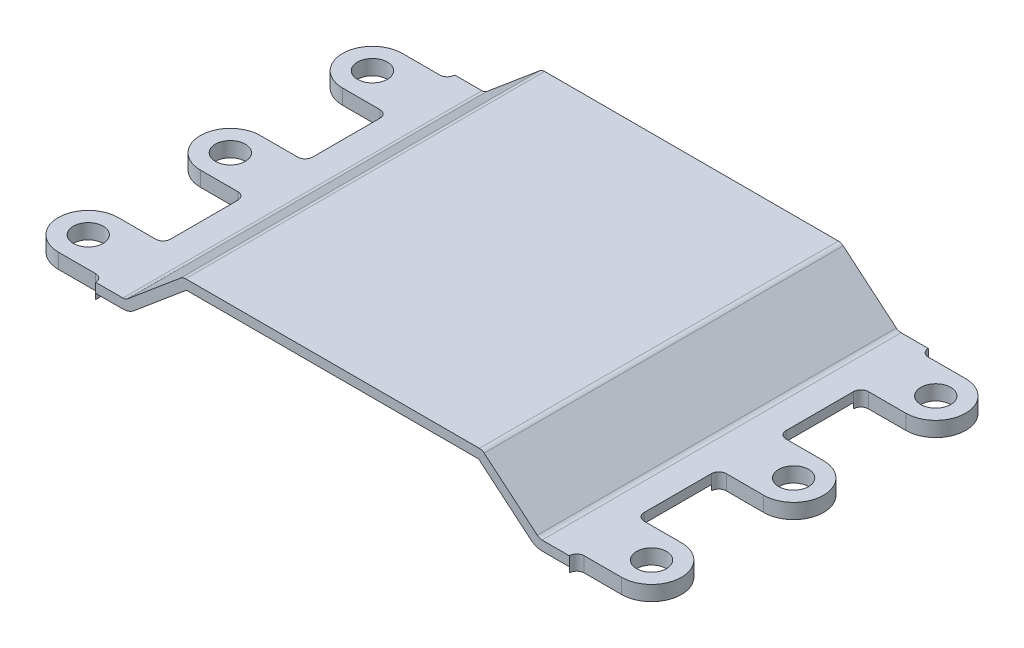
SolidWorks part; units mm, degrees
ref_plane "Front Plane" through (0, 0, 0) normal (0, 0, 1) x (1, 0, 0)
ref_plane "Top Plane" through (0, 0, 0) normal (0, 1, 0) x (1, 0, 0)
ref_plane "Right Plane" through (0, 0, 0) normal (1, 0, 0) x (0, 0, -1)
sketch "Sketch1" plane through (0, 0, 0) normal (0, 0, 1) x (1, 0, 0)
  line L0 (92.7015, 0) -> (86.9293, 0)
  line L1 (85.9089, 0.3714) -> (74.6414, 9.826)
  line L2 (73.621, 10.1974) -> (11.2766, 10.1974)
  line L3 (42.4488, 10.1974) -> (42.4488, 47.8596) construction
  line L4 (-7.804, 0) -> (-2.0318, 0)
  line L5 (-1.0114, 0.3714) -> (10.2561, 9.826)
  arc A0 (-2.0318, 0) -> (-1.0114, 0.3714) centre (-2.0318, 1.5875) ccw
  arc A1 (10.2561, 9.826) -> (11.2766, 10.1974) centre (11.2766, 8.6099) cw
  arc A2 (74.6414, 9.826) -> (73.621, 10.1974) centre (73.621, 8.6099) ccw
  arc A3 (86.9293, 0) -> (85.9089, 0.3714) centre (86.9293, 1.5875) cw
  point P11 (-1.454, 0)
  point P14 (10.6988, 10.1974)
  point P17 (74.1988, 10.1974)
  point P20 (86.3515, 0)
  dimension "D4" = 1.5875
  dimension "D1" = 31.75
  dimension "D2" = 6.35
  dimension "D3" = 40
extrude "Extrude-Thin1" add sketch "Sketch1" against normal blind 76.2 thin
sketch "Sketch2" plane through (0, 0, 0) normal (0, 1, 0) x (1, 0, 0)
  line L0 (92.7015, 0) -> (102.2265, 0) construction
  line L1 (94.289, 1.5875) -> (102.2265, 1.5875)
  line L2 (94.289, 14.2875) -> (102.2265, 14.2875)
  line L3 (92.7015, 15.875) -> (92.7015, 0)
  line L4 (86.3515, 7.9375) -> (102.2265, 7.9375) construction
  line L5 (86.3515, 7.9375) -> (86.3515, 0) construction
  line L8 (94.289, 1.5875) -> (94.289, 0) construction
  line L10 (92.7015, 1.5875) -> (102.2265, 1.5875) construction
  line L11 (92.7015, 1.5875) -> (92.7015, 0) construction
  arc A0 (102.2265, 1.5875) -> (102.2265, 14.2875) centre (102.2265, 7.9375) ccw
  arc A1 (94.289, 1.5875) -> (92.7015, 0) centre (94.289, 0) ccw
  arc A2 (94.289, 14.2875) -> (92.7015, 15.875) centre (94.289, 15.875) cw
  circle A3 centre (102.2265, 7.9375) radius 3.175
  dimension "D2" = 6.35
  dimension "D3" = 6.35
  dimension "D1" = 1.5875
extrude "Boss-Extrude1" add sketch "Sketch2" against normal blind 3.175
sketch "Sketch3" plane through (0, 0, 0) normal (0, 1, 0) x (1, 0, 0)
  line L0 (42.4488, 0) -> (42.4488, 76.2) construction
  line L1 (11.2766, 0) -> (73.621, 0) construction
  line L2 (11.2766, 76.2) -> (73.621, 76.2) construction
ref_plane "Plane1" through (42.4488, 0, 0) normal (1, 0, 0) x (0, 0, -1)
mirror "Mirror1" about plane through (42.4488, 0, 0) normal (1, 0, 0) of "Boss-Extrude1"
pattern_linear "LPattern1" count 3 spacing 30.1625 along (0, 0, -1) of "Boss-Extrude1", "Mirror1"
